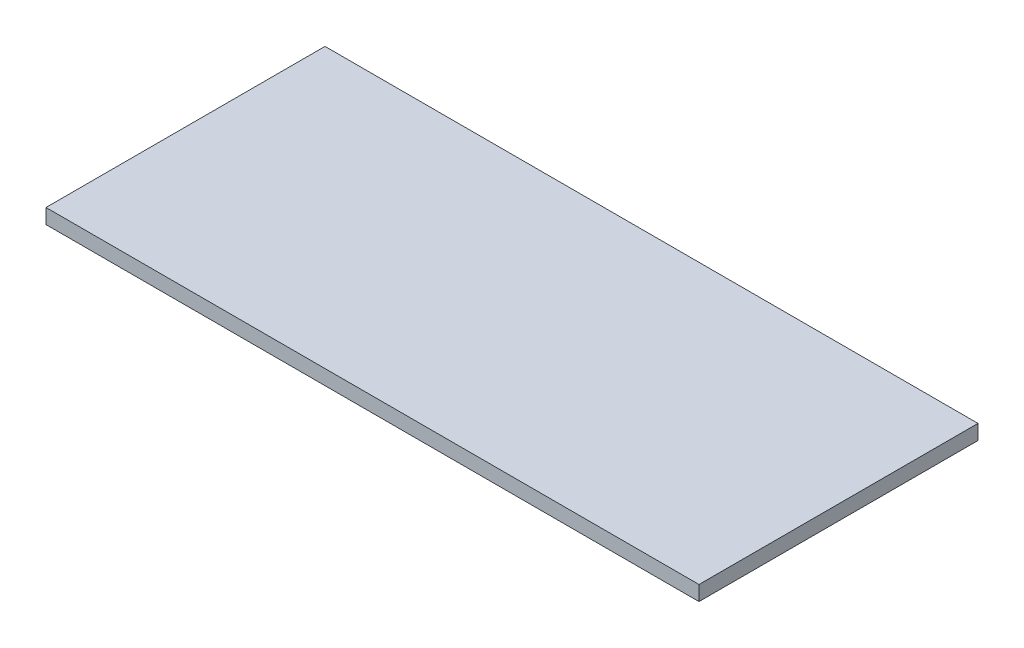
SolidWorks part; units mm, degrees
ref_plane "Front Plane" through (0, 0, 0) normal (0, 0, 1) x (1, 0, 0)
ref_plane "Top Plane" through (0, 0, 0) normal (0, 1, 0) x (1, 0, 0)
ref_plane "Right Plane" through (0, 0, 0) normal (1, 0, 0) x (0, 0, -1)
sketch "Sketch1" plane through (0, 0, 0) normal (0, 1, 0) x (1, 0, 0)
  line L1 (0, 0) -> (279.4, 0)
  line L2 (0, 0) -> (0, 119.38)
  line L3 (0, 119.38) -> (279.4, 119.38)
  line L4 (279.4, 0) -> (279.4, 119.38)
  dimension "D1" = 279.4
  dimension "D2" = 119.38
extrude "Boss-Extrude1" add sketch "Sketch1" along normal blind 6.35
